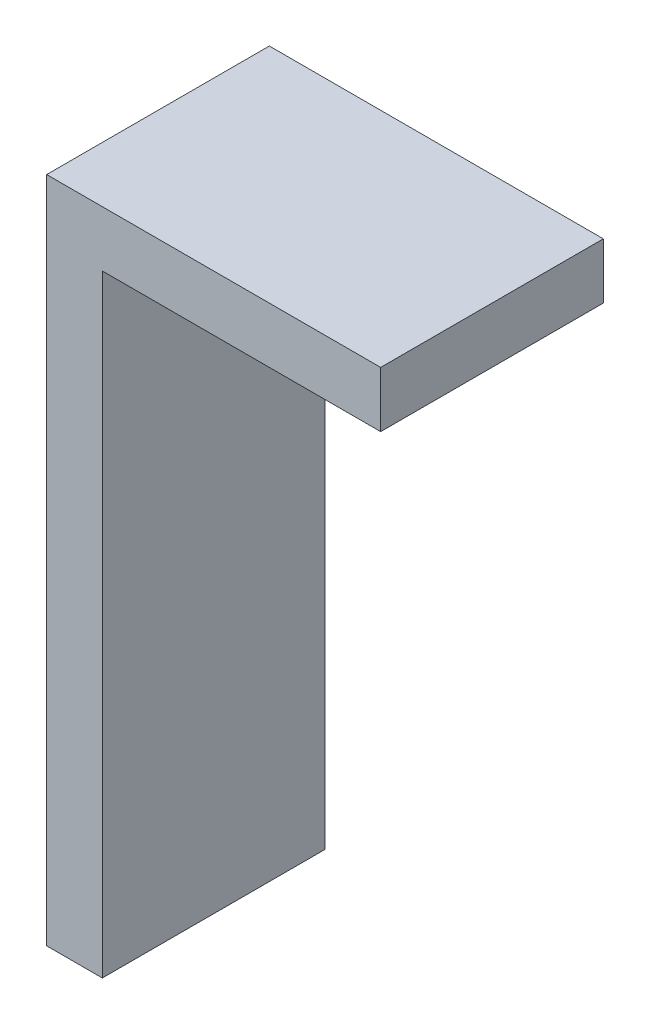
SolidWorks part; units mm, degrees
ref_plane "Front Plane" through (0, 0, 0) normal (0, 0, 1) x (1, 0, 0)
ref_plane "Top Plane" through (0, 0, 0) normal (0, 1, 0) x (1, 0, 0)
ref_plane "Right Plane" through (0, 0, 0) normal (1, 0, 0) x (0, 0, -1)
sketch "Sketch2" plane through (0, 0, 0) normal (0, 1, 0) x (1, 0, 0)
  line L1 (-3.175, -12.7) -> (3.175, -12.7)
  line L2 (-3.175, -12.7) -> (-3.175, 12.7)
  line L3 (-3.175, 12.7) -> (3.175, 12.7)
  line L4 (3.175, -12.7) -> (3.175, 12.7)
  line L5 (-3.175, -12.7) -> (3.175, 12.7) construction
  line L6 (-3.175, 12.7) -> (3.175, -12.7) construction
  point P0 (0, 0)
  dimension "D1" = 25.4
  dimension "D2" = 6.35
extrude "Boss-Extrude1" add sketch "Sketch2" along normal blind 76.2
sketch "Sketch3" plane through (3.175, 0, 0) normal (1, 0, 0) x (0, 0, -1)
  line L0 (12.7, 76.2) -> (12.7, 69.85)
  line L1 (12.7, 76.2) -> (12.7, 0) construction
  line L2 (12.7, 69.85) -> (-12.7, 69.85)
  line L3 (-12.7, 76.2) -> (-12.7, 0) construction
  line L4 (-12.7, 69.85) -> (-12.7, 76.2)
  line L5 (-12.7, 76.2) -> (12.7, 76.2)
  dimension "D1" = 6.35
  dimension "D2" = 25.4
extrude "Boss-Extrude3" add sketch "Sketch3" along normal blind 31.75
